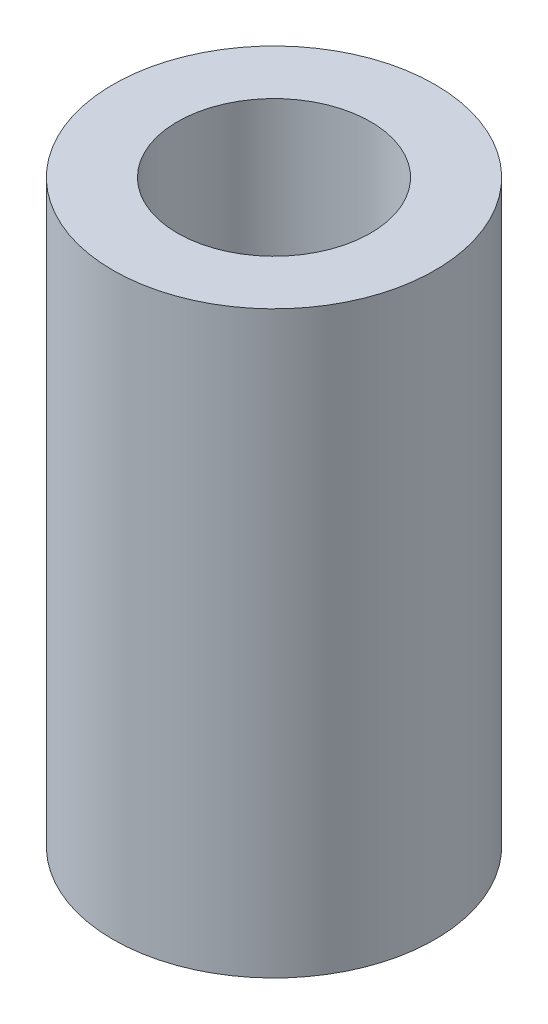
SolidWorks part; units mm, degrees
ref_plane "Plano frontal" through (0, 0, 0) normal (0, 0, 1) x (1, 0, 0)
ref_plane "Plano superior" through (0, 0, 0) normal (0, 1, 0) x (1, 0, 0)
ref_plane "Plano direito" through (0, 0, 0) normal (1, 0, 0) x (0, 0, -1)
sketch "Esboço1" plane through (0, 0, 0) normal (0, 1, 0) x (1, 0, 0)
  circle A0 centre (0, 0) radius 5
  dimension "D1" = 10
extrude "Ressalto-extrusão1" add sketch "Esboço1" along normal blind 3
sketch "Esboço2" plane through (0, 3, 0) normal (0, 1, 0) x (1, 0, 0)
  circle A0 centre (0, 0) radius 5
  circle A1 centre (0, 0) radius 3
  circle A2 centre (0, 0) radius 5 construction
  dimension "D1" = 6
extrude "Ressalto-extrusão2" add sketch "Esboço2" along normal blind 15
hole_wizard "Furo com folga de M2.51" positions "3DSketch1" profile "Esboço3" hole size "M2.5" standard "ISO"
sketch3d "3DSketch1"
  point P0 (0, 0, 0)
  point P3 (0, 0, 0)
sketch "Esboço3" plane through (0, 0, 0) normal (1, 0, 0) x (0, 0, -1)
  line L0 (0, 0) -> (0, 4.8712)
  line L1 (0, 4.8712) -> (1.45, 4)
  line L2 (1.45, 4) -> (1.45, 0)
  line L5 (1.45, 0) -> (0, 0)
  line L10 (0, 4.8712) -> (-1.45, 4) construction
  line L11 (0, -6.35) -> (0, 107.95) construction
  dimension "Hole Dia." = 2.9
  dimension "Hole Depth" = 4
  dimension "Drill Angle" = 118
